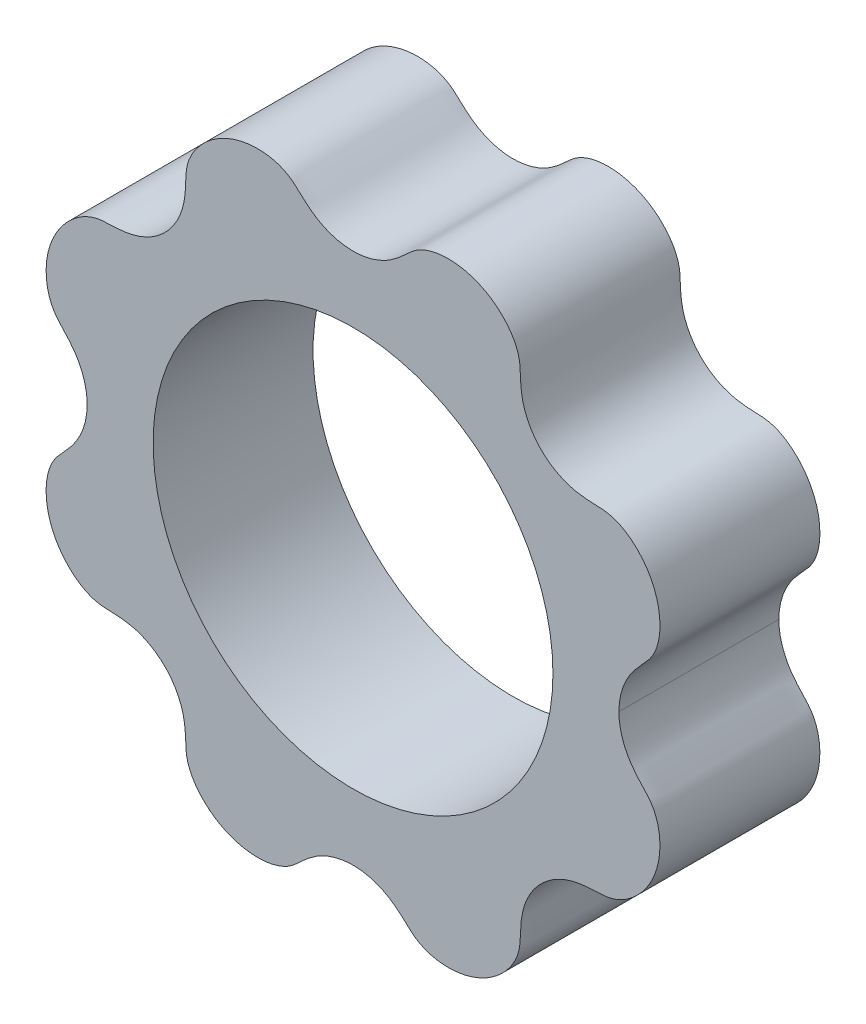
SolidWorks part; units mm, degrees
ref_plane "Plan de face" through (0, 0, 0) normal (0, 0, 1) x (1, 0, 0)
ref_plane "Plan de dessus" through (0, 0, 0) normal (0, 1, 0) x (1, 0, 0)
ref_plane "Plan de droite" through (0, 0, 0) normal (1, 0, 0) x (0, 0, -1)
sketch "Esquisse1" plane through (0, 0, 0) normal (0, 0, 1) x (1, 0, 0)
  line L0 (-1000, 0) -> (49000, 0) construction
  circle A0 centre (0, 0) radius 5
  spline S0 degree 4 poles (7.6842, 1.8231) (7.6652, 1.7682) (7.6215, 1.6608) (7.5454, 1.5163) (7.4151, 1.3527) (7.2756, 1.2143) (7.1515, 1.0775) (7.0333, 0.9228) (6.9422, 0.7713) (6.8749, 0.6279) (6.8271, 0.4963) (6.7962, 0.388) (6.7758, 0.2934) (6.7631, 0.2106) (6.7543, 0.1225) (6.75, 0.0417) (6.7493, -0.016) (6.7526, -0.0954) (6.7584, -0.1681) (6.7691, -0.2544) (6.7876, -0.3523) (6.8223, -0.487) (6.8832, -0.6519) (6.9676, -0.8192) (7.0776, -0.9845) (7.1979, -1.1311) (7.3231, -1.2613) (7.4545, -1.3969) (7.569, -1.5577) (7.6642, -1.7497) (7.7347, -1.9702) (7.7819, -2.2509) (7.7812, -2.5896) (7.7114, -2.9559) (7.5574, -3.3328) (7.3245, -3.6871) (7.0279, -3.9796) (6.6977, -4.1783) (6.3562, -4.282) (6.0589, -4.2867) (5.7916, -4.2922) (5.4965, -4.3442) (5.1863, -4.4562) (4.8418, -4.674) (4.5827, -4.9639) (4.4241, -5.2632) (4.3402, -5.538) (4.3047, -5.7268) (4.2891, -5.9078) (4.2865, -6.0792) (4.2818, -6.2784) (4.2437, -6.4909) (4.1578, -6.717) (3.9908, -6.9991) (3.7392, -7.2815) (3.4049, -7.5248) (2.9934, -7.701) (2.5592, -7.7877) (2.1409, -7.7814) (1.7662, -7.685) (1.4523, -7.5126) (1.2397, -7.3004) (1.0443, -7.1179) (0.7969, -6.9482) (0.4958, -6.8113) (0.0993, -6.7275) (-0.287, -6.7543) (-0.6062, -6.8557) (-0.8541, -6.9894) (-1.0111, -7.0976) (-1.1484, -7.2139) (-1.2697, -7.3317) (-1.4114, -7.4665) (-1.5845, -7.5875) (-1.7996, -7.6856) (-2.1118, -7.7685) (-2.4857, -7.7938) (-2.9059, -7.7319) (-3.3456, -7.5567) (-3.6842, -7.3239) (-3.9278, -7.0752) (-4.093, -6.8347) (-4.1966, -6.6224) (-4.2613, -6.4122) (-4.2863, -6.2108) (-4.286, -6.0182) (-4.2936, -5.8353) (-4.3175, -5.644) (-4.3643, -5.4467) (-4.4575, -5.1956) (-4.621, -4.9201) (-4.8694, -4.6566) (-5.1863, -4.4562) (-5.4965, -4.3442) (-5.7916, -4.2922) (-6.0589, -4.2867) (-6.3562, -4.282) (-6.6977, -4.1783) (-7.0279, -3.9796) (-7.3245, -3.6871) (-7.5602, -3.3286) (-7.7167, -2.942) (-7.7848, -2.565) (-7.7796, -2.2166) (-7.7247, -1.9298) (-7.6466, -1.707) (-7.5419, -1.5122) (-7.4141, -1.3514) (-7.2749, -1.2137) (-7.1492, -1.0749) (-7.0305, -0.9188) (-6.9397, -0.7665) (-6.8729, -0.6231) (-6.8259, -0.4924) (-6.7955, -0.385) (-6.7725, -0.2772) (-6.7571, -0.1688) (-6.7493, -0.04) (-6.7494, 0.0407) (-6.7562, 0.1542) (-6.767, 0.2384) (-6.7816, 0.3203) (-6.8001, 0.4016) (-6.8271, 0.4963) (-6.8749, 0.6279) (-6.9422, 0.7713) (-7.0333, 0.9228) (-7.1515, 1.0775) (-7.2756, 1.2143) (-7.4151, 1.3527) (-7.5454, 1.5163) (-7.6215, 1.6608) (-7.6652, 1.7682) (-7.6842, 1.8231) knots 0 0 0 0 0 0.007275 0.01455 0.020335 0.026121 0.031906 0.037692 0.044714 0.048225 0.051736 0.055247 0.058758 0.060513 0.062269 0.06578 0.067901 0.070022 0.072144 0.074265 0.078507 0.08275 0.08951 0.096269 0.101933 0.107597 0.11326 0.118924 0.125575 0.132225 0.140035 0.147844 0.161146 0.174447 0.186485 0.198523 0.214075 0.226115 0.234386 0.242656 0.251172 0.259688 0.271735 0.283795 0.30174 0.307748 0.313755 0.319763 0.325771 0.330509 0.335248 0.344725 0.352681 0.360637 0.376209 0.391782 0.404039 0.416296 0.431439 0.443698 0.452127 0.460556 0.468911 0.477266 0.489531 0.50181 0.519177 0.525142 0.531107 0.537072 0.543037 0.547674 0.55231 0.561584 0.569358 0.577131 0.592675 0.608218 0.622095 0.635971 0.643793 0.651614 0.658553 0.665492 0.671225 0.676958 0.682691 0.688424 0.695368 0.702313 0.716205 0.728265 0.740312 0.748828 0.757344 0.765614 0.773885 0.785925 0.801477 0.813515 0.825553 0.839472 0.85339 0.861188 0.868986 0.875945 0.882903 0.888767 0.894631 0.900495 0.906359 0.913325 0.916808 0.920291 0.923773 0.927256 0.930738 0.93422 0.937731 0.941242 0.942998 0.944753 0.948264 0.951775 0.955286 0.962308 0.968094 0.973879 0.979665 0.98545 0.992725 1 1 1 1 1 construction
  spline S1 degree 4 poles (6.75, 0) (6.75, -0.0147) (6.7505, -0.0442) (6.7526, -0.0954) (6.7584, -0.1681) (6.7691, -0.2544) (6.7876, -0.3523) (6.8223, -0.487) (6.8832, -0.6519) (6.9676, -0.8192) (7.0776, -0.9845) (7.1979, -1.1311) (7.3231, -1.2613) (7.4545, -1.3969) (7.569, -1.5577) (7.6642, -1.7497) (7.7347, -1.9702) (7.7819, -2.2509) (7.7812, -2.5896) (7.7114, -2.9559) (7.5574, -3.3328) (7.3245, -3.6871) (7.0279, -3.9796) (6.6977, -4.1783) (6.3562, -4.282) (6.0589, -4.2867) (5.7916, -4.2922) (5.4965, -4.3442) (5.1863, -4.4562) (4.8418, -4.674) (4.5827, -4.9639) (4.4241, -5.2632) (4.3402, -5.538) (4.3047, -5.7268) (4.2891, -5.9078) (4.2865, -6.0792) (4.2818, -6.2784) (4.2437, -6.4909) (4.1578, -6.717) (3.9908, -6.9991) (3.7392, -7.2815) (3.4049, -7.5248) (2.9934, -7.701) (2.5592, -7.7877) (2.1409, -7.7814) (1.7662, -7.685) (1.4523, -7.5126) (1.2397, -7.3004) (1.0443, -7.1179) (0.7969, -6.9482) (0.4958, -6.8113) (0.0993, -6.7275) (-0.287, -6.7543) (-0.6062, -6.8557) (-0.8541, -6.9894) (-1.0111, -7.0976) (-1.1484, -7.2139) (-1.2697, -7.3317) (-1.4114, -7.4665) (-1.5845, -7.5875) (-1.7996, -7.6856) (-2.1118, -7.7685) (-2.4857, -7.7938) (-2.9059, -7.7319) (-3.3456, -7.5567) (-3.6842, -7.3239) (-3.9278, -7.0752) (-4.093, -6.8347) (-4.1966, -6.6224) (-4.2613, -6.4122) (-4.2863, -6.2108) (-4.286, -6.0182) (-4.2936, -5.8353) (-4.3175, -5.644) (-4.3643, -5.4467) (-4.4575, -5.1956) (-4.621, -4.9201) (-4.8694, -4.6566) (-5.1863, -4.4562) (-5.4965, -4.3442) (-5.7916, -4.2922) (-6.0589, -4.2867) (-6.3562, -4.282) (-6.6977, -4.1783) (-7.0279, -3.9796) (-7.3245, -3.6871) (-7.5602, -3.3286) (-7.7167, -2.942) (-7.7848, -2.565) (-7.7796, -2.2166) (-7.7247, -1.9298) (-7.6466, -1.707) (-7.5419, -1.5122) (-7.4141, -1.3514) (-7.2749, -1.2137) (-7.1492, -1.0749) (-7.0305, -0.9188) (-6.9397, -0.7665) (-6.8729, -0.6231) (-6.8259, -0.4924) (-6.7955, -0.385) (-6.7725, -0.2772) (-6.7571, -0.1688) (-6.7513, -0.0724) (-6.75, -0.0241) (-6.75, 0) knots 0.06578 0.06578 0.06578 0.06578 0.06578 0.067901 0.070022 0.072144 0.074265 0.078507 0.08275 0.08951 0.096269 0.101933 0.107597 0.11326 0.118924 0.125575 0.132225 0.140035 0.147844 0.161146 0.174447 0.186485 0.198523 0.214075 0.226115 0.234386 0.242656 0.251172 0.259688 0.271735 0.283795 0.30174 0.307748 0.313755 0.319763 0.325771 0.330509 0.335248 0.344725 0.352681 0.360637 0.376209 0.391782 0.404039 0.416296 0.431439 0.443698 0.452127 0.460556 0.468911 0.477266 0.489531 0.50181 0.519177 0.525142 0.531107 0.537072 0.543037 0.547674 0.55231 0.561584 0.569358 0.577131 0.592675 0.608218 0.622095 0.635971 0.643793 0.651614 0.658553 0.665492 0.671225 0.676958 0.682691 0.688424 0.695368 0.702313 0.716205 0.728265 0.740312 0.748828 0.757344 0.765614 0.773885 0.785925 0.801477 0.813515 0.825553 0.839472 0.85339 0.861188 0.868986 0.875945 0.882903 0.888767 0.894631 0.900495 0.906359 0.913325 0.916808 0.920291 0.923773 0.927256 0.930738 0.93422 0.93422 0.93422 0.93422 0.93422 construction
  spline S2 degree 4 poles (6.75, 0) (6.75, 0.0147) (6.7505, 0.0442) (6.7526, 0.0954) (6.7584, 0.1681) (6.7691, 0.2544) (6.7876, 0.3523) (6.8223, 0.487) (6.8832, 0.6519) (6.9676, 0.8192) (7.0776, 0.9845) (7.1979, 1.1311) (7.3231, 1.2613) (7.4545, 1.3969) (7.569, 1.5577) (7.6642, 1.7497) (7.7347, 1.9702) (7.7819, 2.2509) (7.7812, 2.5896) (7.7114, 2.9559) (7.5574, 3.3328) (7.3245, 3.6871) (7.0279, 3.9796) (6.6977, 4.1783) (6.3562, 4.282) (6.0589, 4.2867) (5.7916, 4.2922) (5.4965, 4.3442) (5.1863, 4.4562) (4.8418, 4.674) (4.5827, 4.9639) (4.4241, 5.2632) (4.3402, 5.538) (4.3047, 5.7268) (4.2891, 5.9078) (4.2865, 6.0792) (4.2818, 6.2784) (4.2437, 6.4909) (4.1578, 6.717) (3.9908, 6.9991) (3.7392, 7.2815) (3.4049, 7.5248) (2.9934, 7.701) (2.5592, 7.7877) (2.1409, 7.7814) (1.7662, 7.685) (1.4523, 7.5126) (1.2397, 7.3004) (1.0443, 7.1179) (0.7969, 6.9482) (0.4958, 6.8113) (0.0993, 6.7275) (-0.287, 6.7543) (-0.6062, 6.8557) (-0.8541, 6.9894) (-1.0111, 7.0976) (-1.1484, 7.2139) (-1.2697, 7.3317) (-1.4114, 7.4665) (-1.5845, 7.5875) (-1.7996, 7.6856) (-2.1118, 7.7685) (-2.4857, 7.7938) (-2.9059, 7.7319) (-3.3456, 7.5567) (-3.6842, 7.3239) (-3.9278, 7.0752) (-4.093, 6.8347) (-4.1966, 6.6224) (-4.2613, 6.4122) (-4.2863, 6.2108) (-4.286, 6.0182) (-4.2936, 5.8353) (-4.3175, 5.644) (-4.3643, 5.4467) (-4.4575, 5.1956) (-4.621, 4.9201) (-4.8694, 4.6566) (-5.1863, 4.4562) (-5.4965, 4.3442) (-5.7916, 4.2922) (-6.0589, 4.2867) (-6.3562, 4.282) (-6.6977, 4.1783) (-7.0279, 3.9796) (-7.3245, 3.6871) (-7.5602, 3.3286) (-7.7167, 2.942) (-7.7848, 2.565) (-7.7796, 2.2166) (-7.7247, 1.9298) (-7.6466, 1.707) (-7.5419, 1.5122) (-7.4141, 1.3514) (-7.2749, 1.2137) (-7.1492, 1.0749) (-7.0305, 0.9188) (-6.9397, 0.7665) (-6.8729, 0.6231) (-6.8259, 0.4924) (-6.7955, 0.385) (-6.7725, 0.2772) (-6.7571, 0.1688) (-6.7513, 0.0724) (-6.75, 0.0241) (-6.75, 0) knots 0.06578 0.06578 0.06578 0.06578 0.06578 0.067901 0.070022 0.072144 0.074265 0.078507 0.08275 0.08951 0.096269 0.101933 0.107597 0.11326 0.118924 0.125575 0.132225 0.140035 0.147844 0.161146 0.174447 0.186485 0.198523 0.214075 0.226115 0.234386 0.242656 0.251172 0.259688 0.271735 0.283795 0.30174 0.307748 0.313755 0.319763 0.325771 0.330509 0.335248 0.344725 0.352681 0.360637 0.376209 0.391782 0.404039 0.416296 0.431439 0.443698 0.452127 0.460556 0.468911 0.477266 0.489531 0.50181 0.519177 0.525142 0.531107 0.537072 0.543037 0.547674 0.55231 0.561584 0.569358 0.577131 0.592675 0.608218 0.622095 0.635971 0.643793 0.651614 0.658553 0.665492 0.671225 0.676958 0.682691 0.688424 0.695368 0.702313 0.716205 0.728265 0.740312 0.748828 0.757344 0.765614 0.773885 0.785925 0.801477 0.813515 0.825553 0.839472 0.85339 0.861188 0.868986 0.875945 0.882903 0.888767 0.894631 0.900495 0.906359 0.913325 0.916808 0.920291 0.923773 0.927256 0.930738 0.93422 0.93422 0.93422 0.93422 0.93422 construction
  spline S3 degree 1 poles (6.65, 0) (-6.65, 0) knots 0 0 1 1 construction
  spline S4 degree 1 poles (6.65, 0) (-6.65, 0) knots 0 0 1 1 construction
  spline S5 degree 3 poles (6.65, 0) (6.65, 0.3027) (6.7761, 0.7653) (7.1618, 1.2501) (7.5595, 1.6349) (7.7352, 2.314) (7.5842, 3.1415) (7.1056, 3.8336) (6.502, 4.1892) (5.9482, 4.1807) (5.3319, 4.2505) (4.6429, 4.6429) (4.2508, 5.3321) (4.1801, 5.9482) (4.1893, 6.5014) (3.8334, 7.1059) (3.1415, 7.5842) (2.3137, 7.7352) (1.6352, 7.5598) (1.2498, 7.162) (0.7647, 6.7759) (-0.0001, 6.566) (-0.7646, 6.7761) (-1.2503, 7.1618) (-1.6349, 7.5595) (-2.3139, 7.7352) (-3.1415, 7.5842) (-3.8334, 7.1058) (-4.1894, 6.5017) (-4.18, 5.9481) (-4.2508, 5.3321) (-4.6429, 4.6429) (-5.3319, 4.2506) (-5.9482, 4.1807) (-6.502, 4.1892) (-7.1056, 3.8336) (-7.5842, 3.1415) (-7.7351, 2.3139) (-7.5598, 1.6351) (-7.1616, 1.2501) (-6.7762, 0.7653) (-6.65, 0.3027) (-6.65, 0) knots 0.06578 0.06578 0.06578 0.06578 0.092918 0.106488 0.120057 0.147196 0.174335 0.201473 0.228612 0.242182 0.255751 0.28289 0.310029 0.323598 0.337167 0.364306 0.391445 0.418584 0.445722 0.459292 0.472861 0.5 0.527139 0.540708 0.554278 0.581416 0.608555 0.635694 0.662833 0.676402 0.689971 0.71711 0.744249 0.757818 0.771388 0.798527 0.825665 0.852804 0.879943 0.893512 0.907082 0.93422 0.93422 0.93422 0.93422
  spline S6 degree 3 poles (-6.65, 0) (-6.65, -0.3027) (-6.7762, -0.7653) (-7.1616, -1.2501) (-7.5598, -1.6351) (-7.7351, -2.3139) (-7.5842, -3.1415) (-7.1056, -3.8336) (-6.502, -4.1892) (-5.9482, -4.1807) (-5.3319, -4.2506) (-4.6429, -4.6429) (-4.2508, -5.3321) (-4.18, -5.9481) (-4.1894, -6.5017) (-3.8334, -7.1058) (-3.1415, -7.5842) (-2.3139, -7.7352) (-1.6349, -7.5595) (-1.2503, -7.1618) (-0.7646, -6.7761) (-0.0001, -6.566) (0.7647, -6.7759) (1.2498, -7.162) (1.6352, -7.5598) (2.3137, -7.7352) (3.1415, -7.5842) (3.8334, -7.1059) (4.1893, -6.5014) (4.1801, -5.9482) (4.2508, -5.3321) (4.6429, -4.6429) (5.3319, -4.2505) (5.9482, -4.1807) (6.502, -4.1892) (7.1056, -3.8336) (7.5842, -3.1415) (7.7352, -2.314) (7.5595, -1.6349) (7.1618, -1.2501) (6.7761, -0.7653) (6.65, -0.3027) (6.65, 0) knots 0.06578 0.06578 0.06578 0.06578 0.092918 0.106488 0.120057 0.147196 0.174335 0.201473 0.228612 0.242182 0.255751 0.28289 0.310029 0.323598 0.337167 0.364306 0.391445 0.418584 0.445722 0.459292 0.472861 0.5 0.527139 0.540708 0.554278 0.581416 0.608555 0.635694 0.662833 0.676402 0.689971 0.71711 0.744249 0.757818 0.771388 0.798527 0.825665 0.852804 0.879943 0.893512 0.907082 0.93422 0.93422 0.93422 0.93422
  dimension "D1" = 10
  dimension "D2" = 0.1
extrude "Boss.-Extru.4" add sketch "Esquisse1" along normal blind 4
equation "\"R\" = 9'Radius of the rotor"
equation "\"E\"= 0.75'Eccentricity from input shaft to center of rotor"
equation "\"Rr\"= 1.5'Roller radius"
equation "\"N\" = 9'Amount of rollers"
